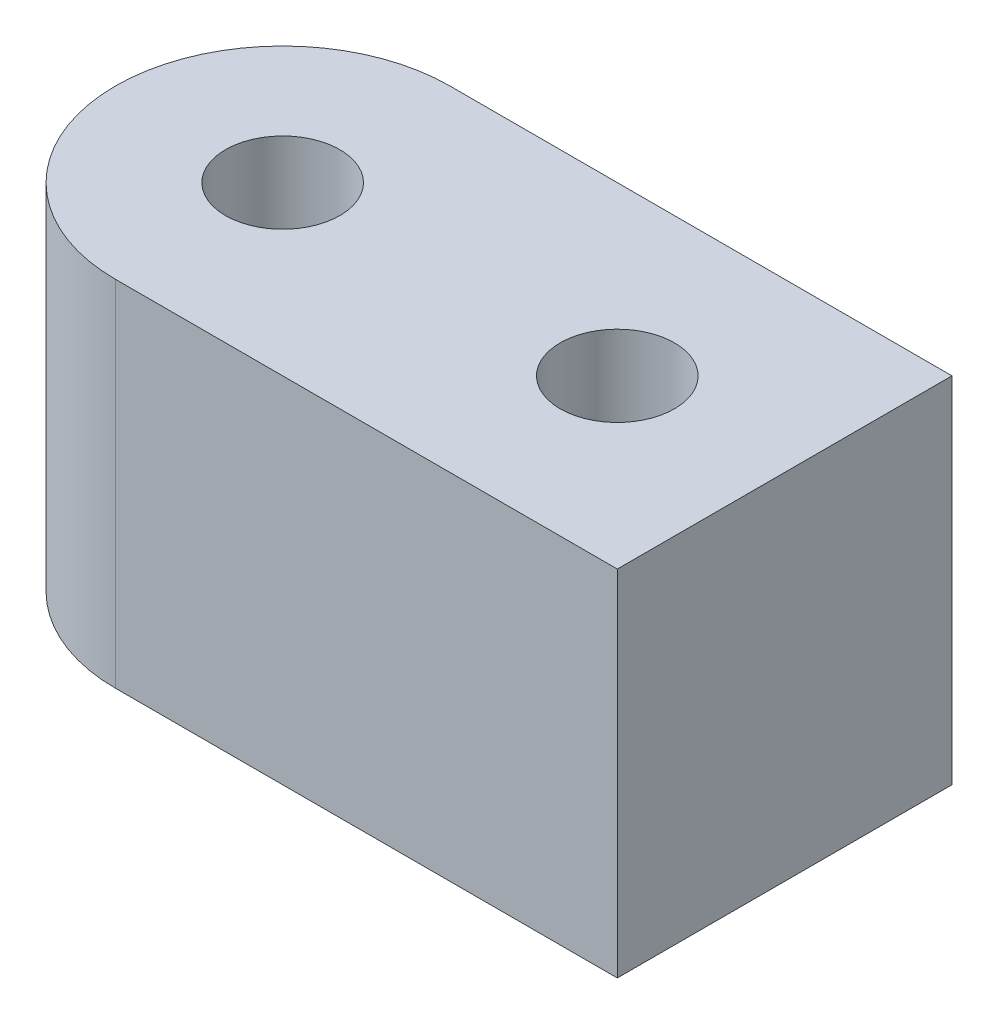
SolidWorks part; units mm, degrees
material "6061 Alloy"
ref_plane "Front Plane" through (0, 0, 0) normal (0, 0, 1) x (1, 0, 0)
ref_plane "Top Plane" through (0, 0, 0) normal (0, 1, 0) x (1, 0, 0)
ref_plane "Right Plane" through (0, 0, 0) normal (1, 0, 0) x (0, 0, -1)
sketch "Sketch1" plane through (0, 0, 0) normal (0, 1, 0) x (1, 0, 0)
  line L0 (6, 6) -> (6, -6)
  line L1 (-18, 0) -> (6, 0) construction
  line L12 (6, 6) -> (-12, 6)
  line L46 (-12, -6) -> (6, -6)
  circle A65 centre (0, 0) radius 2.05
  circle A87 centre (-12, 0) radius 2.05
  arc A88 (-12, 6) -> (-12, -6) centre (-12, 0) ccw
  dimension "D13" = 12
  dimension "D11" = 4.1
  dimension "D14" = 12
  dimension "D2" = 6
extrude "Boss-Extrude1" add sketch "Sketch1" along normal blind 12.7
